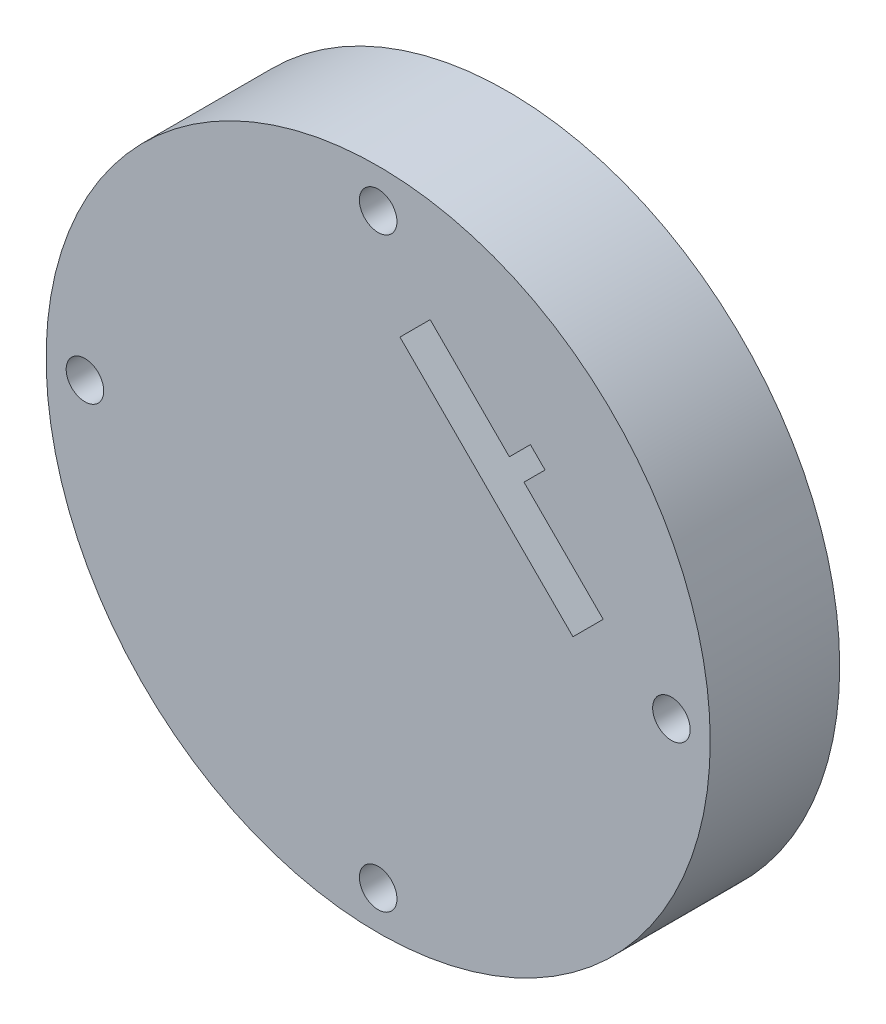
SolidWorks part; units mm, degrees
ref_plane "Front Plane" through (0, 0, 0) normal (0, 0, 1) x (1, 0, 0)
ref_plane "Top Plane" through (0, 0, 0) normal (0, 1, 0) x (1, 0, 0)
ref_plane "Right Plane" through (0, 0, 0) normal (1, 0, 0) x (0, 0, -1)
sketch "Sketch1" plane through (0, 0, 0) normal (0, 0, 1) x (1, 0, 0)
  circle A0 centre (0, 0) radius 25.65
  circle A2 centre (0, -22.65) radius 1.45
  circle A3 centre (0, -22.65) radius 1.45
  circle A4 centre (22.65, 0) radius 1.45
  circle A5 centre (22.65, 0) radius 1.45
  circle A6 centre (0, 22.65) radius 1.45
  circle A7 centre (0, 22.65) radius 1.45
  circle A8 centre (-22.65, 0) radius 1.45
  circle A9 centre (-22.65, 0) radius 1.45
  dimension "D1" = 0
  dimension "D2" = 0
  dimension "D3" = 0
  dimension "D4" = 0
extrude "Boss-Extrude1" add sketch "Sketch1" along normal blind 10 contours A0
sketch "Sketch2" plane through (0, 0, 10) normal (0, 0, 1) x (1, 0, 0)
  line L0 (0, 0) -> (18.1373, 18.1373) construction
  line L1 (1.6829, 15.0472) -> (15.0472, 1.6829)
  line L2 (15.0472, 1.6829) -> (18.5461, 5.1818) construction
  line L3 (4.0164, 17.3807) -> (17.3807, 4.0164) construction
  line L4 (17.3807, 4.0164) -> (15.0472, 1.6829)
  line L5 (4.0164, 17.3807) -> (1.6829, 15.0472)
  line L6 (11.2642, 10.1328) -> (12.8906, 11.7592)
  line L7 (12.8906, 11.7592) -> (11.7592, 12.8906)
  line L8 (10.6985, 10.6985) -> (11.2642, 10.1328) construction
  line L9 (10.1328, 11.2642) -> (11.2642, 10.1328) construction
  line L10 (10.1328, 11.2642) -> (11.7592, 12.8906)
  line L11 (17.3807, 4.0164) -> (11.2642, 10.1328)
  line L12 (10.1328, 11.2642) -> (4.0164, 17.3807)
  circle A0 centre (0, 0) radius 25.65 construction
  point P5 (10.6985, 10.6985)
  point P6 (8.3651, 8.3651)
  point P13 (10.6985, 10.6985)
  point P14 (8.3651, 8.3651)
  point P19 (12.3249, 12.3249)
  dimension "D1" = 10.52
  dimension "D2" = 3.3
  dimension "D3" = 18.9
  dimension "D4" = 2.3
  dimension "D5" = 1.6
extrude "Cut-Extrude1" cut sketch "Sketch2" against normal blind 7.5
